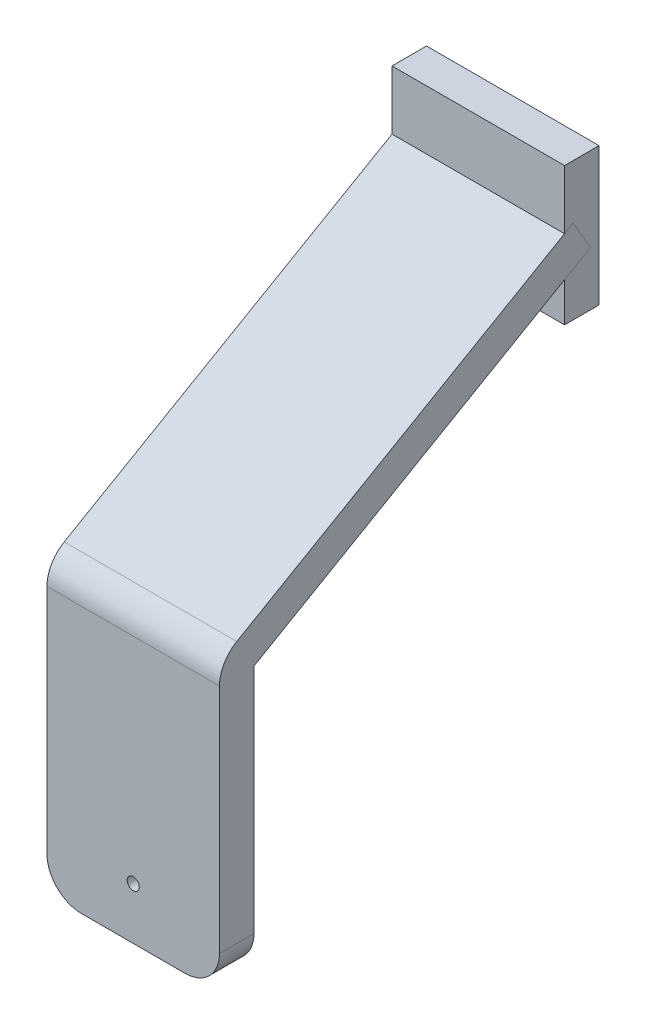
SolidWorks part; units mm, degrees
ref_plane "Front Plane" through (0, 0, 0) normal (1, 0, 0) x (0, 1, 0)
ref_plane "Top Plane" through (0, 0, 0) normal (0, 0, 1) x (0, 1, 0)
ref_plane "Right Plane" through (0, 0, 0) normal (0, 1, 0) x (-1, 0, 0)
sketch "Sketch2" plane through (0, 0, 0) normal (1, 0, 0) x (0, 1, 0)
  line L0 (0, 0) -> (80, 0)
  line L1 (80, 0) -> (137.735, -100)
  line L2 (117.735, -100) -> (157.735, -100)
  point P3 (137.735, -100)
  dimension "D1" = 80
  dimension "D2" = 60
  dimension "D3" = 100
  dimension "D4" = 40
extrude "Extrude-Thin1" add sketch "Sketch2" along normal blind 50 thin thin type mid plane wall 10
fillet "Fillet2" radius 10 2 edges at (0, 0, 0) (50, 0, 0)
fillet "Fillet3" radius 10 1 edges at (25, 82.8868, 5)
sketch "Sketch3" plane through (0, 0, 0) normal (0, 0, 1) x (0, 1, 0)
  line L0 (0, -25) -> (30, -25) construction
  line L1 (0, -40) -> (0, -10) construction
  circle A0 centre (15, -25) radius 1.75
  dimension "D1" = 15
  dimension "D2" = 3.5
extrude "Cut-Extrude1" cut sketch "Sketch3" against normal up to next (5 mm away) and the other way through all
